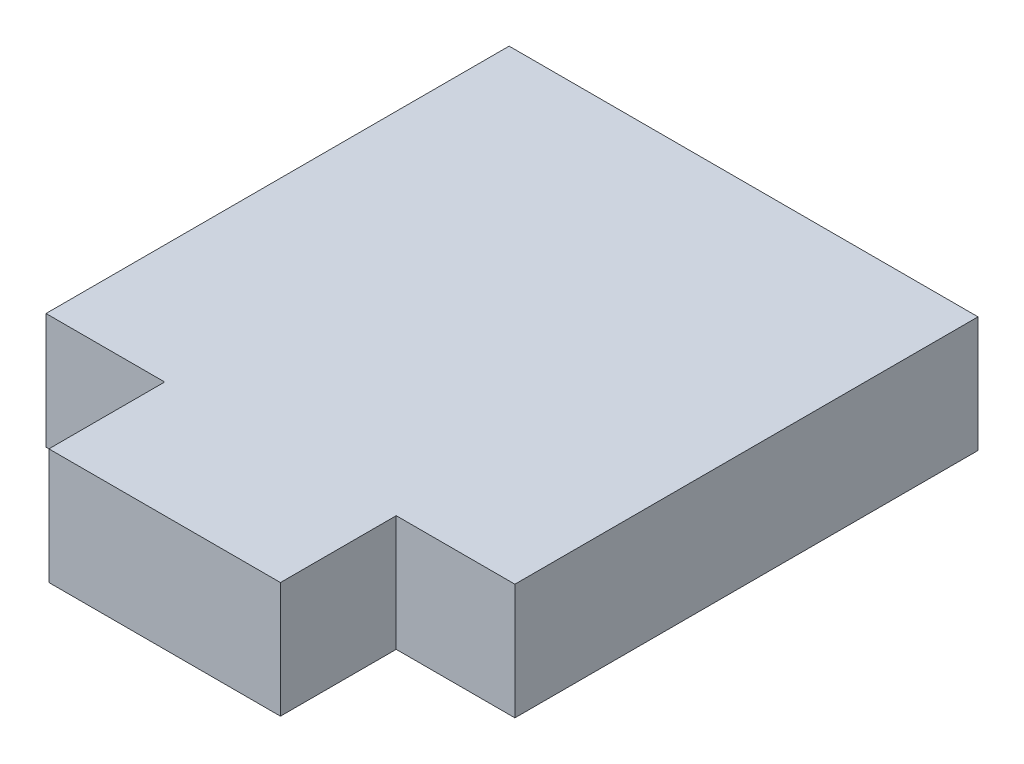
SolidWorks part; units mm, degrees
material "Maple"
ref_plane "Front Plane" through (0, 0, 0) normal (0, 0, 1) x (1, 0, 0)
ref_plane "Top Plane" through (0, 0, 0) normal (0, 1, 0) x (1, 0, 0)
ref_plane "Right Plane" through (0, 0, 0) normal (1, 0, 0) x (0, 0, -1)
sketch "Sketch1" plane through (0, 0, 0) normal (0, 1, 0) x (1, 0, 0)
  line L0 (-25.7175, 0) -> (0, 25.4) construction
  line L1 (0, 0) -> (-25.7175, 0) construction
  line L2 (0, 0) -> (0, 25.4) construction
  line L3 (0, 25.4) -> (-25.7175, 25.4) construction
  line L4 (-25.7175, 0) -> (-25.7175, 25.4) construction
  line L5 (-19.2087, 0) -> (-6.5087, 0) construction
  line L6 (-19.2087, 0) -> (-19.2087, -6.35) construction
  line L7 (-19.2087, -6.35) -> (-6.5087, -6.35) construction
  line L8 (-6.5087, 0) -> (-6.5087, -6.35) construction
  line L9 (-19.2087, -6.35) -> (-6.5087, 0) construction
  line L10 (-25.7175, 25.4) -> (0, 25.4)
  line L11 (0, 25.4) -> (0, 0)
  line L12 (0, 0) -> (-6.5087, 0)
  line L13 (-6.5087, 0) -> (-6.5087, -6.35)
  line L14 (-6.5087, -6.35) -> (-19.2087, -6.35)
  line L15 (-19.2087, -6.35) -> (-19.2087, 0)
  line L16 (-19.2087, 0) -> (-25.7175, 0)
  line L17 (-25.7175, 0) -> (-25.7175, 25.4)
  point P9 (-12.8587, -3.175)
  point P10 (-12.8587, 12.7)
  dimension "D1" = 25.4
  dimension "D2" = 25.7175
  dimension "D3" = 6.35
  dimension "D4" = 12.7
extrude "Boss-Extrude1" add sketch "Sketch1" along normal blind 6.35
